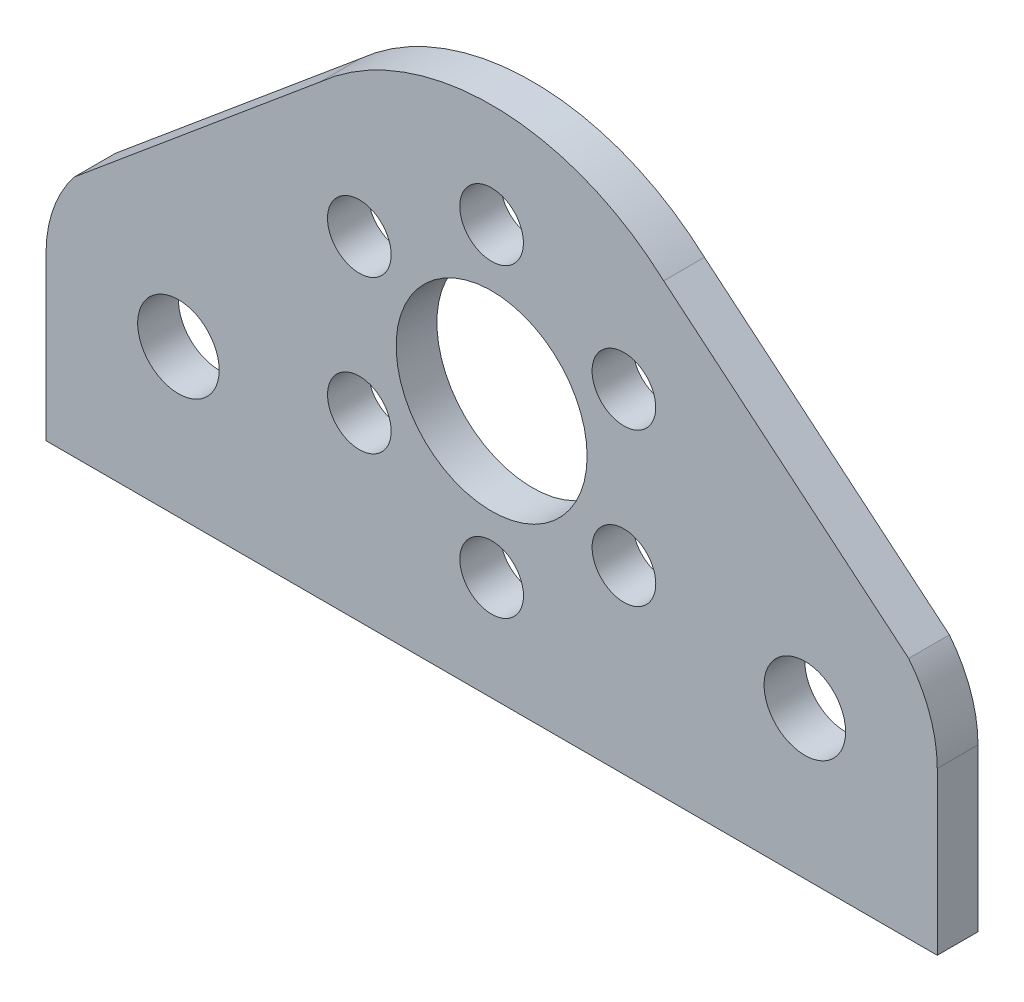
SolidWorks part; units mm, degrees
ref_plane "Alzado" through (0, 0, 0) normal (0, 0, 1) x (1, 0, 0)
ref_plane "Planta" through (0, 0, 0) normal (0, 1, 0) x (1, 0, 0)
ref_plane "Vista lateral" through (0, 0, 0) normal (1, 0, 0) x (0, 0, -1)
sketch "Croquis1" plane through (0, 0, 0) normal (0, 0, 1) x (1, 0, 0)
  line L4 (0, 0) -> (0, 1.5946) construction
  line L17 (-17.5, -10.1) -> (17.5, -10.1)
  line L18 (0, -10.1) -> (0, -9.9022) construction
  line L21 (-17.5, -10.1) -> (-17.5, -3.744)
  line L23 (17.5, -10.1) -> (17.5, -3.744)
  line L25 (0, 11.4788) -> (0, -10.1) construction
  line L26 (-16.3755, -0.5624) -> (-6.7575, 7.4663)
  line L28 (16.3755, -0.5624) -> (6.7575, 7.4663)
  circle A8 centre (0, 0) radius 3.75
  circle A12 centre (-0.0012, 5.9988) radius 1.25
  circle A13 centre (5.1945, 3.0004) radius 1.25
  circle A14 centre (5.1957, -2.9984) radius 1.25
  circle A15 centre (0.0012, -5.9988) radius 1.25
  circle A16 centre (-5.1945, -3.0004) radius 1.25
  circle A17 centre (-5.1957, 2.9984) radius 1.25
  circle A19 centre (12.3, -4.3) radius 1.6
  circle A21 centre (-12.3, -4.3) radius 1.6
  arc A32 (-17.5, -3.744) -> (-16.3755, -0.5624) centre (-12.4368, -3.744) cw
  arc A35 (17.5, -3.744) -> (16.3755, -0.5624) centre (12.4368, -3.744) ccw
  arc A36 (6.7575, 7.4663) -> (-6.7575, 7.4663) centre (0, 0) ccw
  point P34 (11.465, -0.5624)
  dimension "D1" = 12.3
  dimension "D2" = 35
  dimension "D7" = 3.2
  dimension "D4" = 4.3
  dimension "D5" = 10.1
  dimension "D6" = 7.5
  dimension "D3" = 2.5
extrude "Saliente-Extruir1" add sketch "Croquis1" along normal blind 1.6
sketch "Croquis2" plane through (0, 0, 1.6) normal (0, 0, 1) x (1, 0, 0)
  circle A0 centre (0, 0) radius 10
  dimension "D1" = 20
